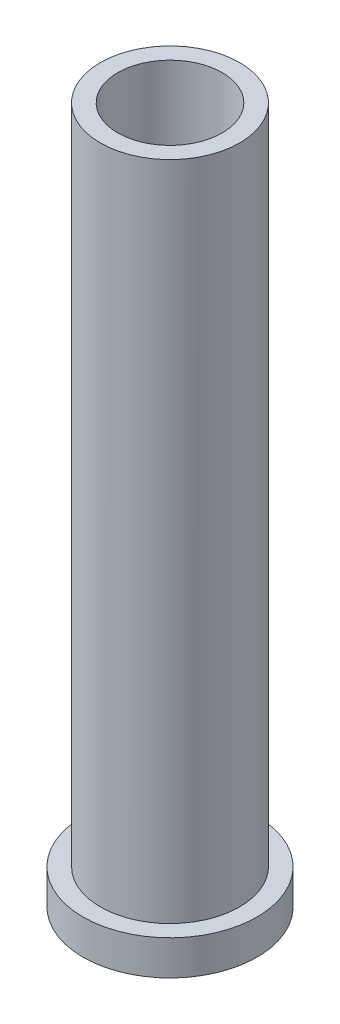
SolidWorks part; units mm, degrees
ref_plane "Front Plane" through (0, 0, 0) normal (0, 0, 1) x (1, 0, 0)
ref_plane "Top Plane" through (0, 0, 0) normal (0, 1, 0) x (1, 0, 0)
ref_plane "Right Plane" through (0, 0, 0) normal (1, 0, 0) x (0, 0, -1)
sketch "Sketch1" plane through (0, 0, 0) normal (0, 1, 0) x (1, 0, 0)
  circle A0 centre (0, 0) radius 4
  dimension "D1" = 8
extrude "Boss-Extrude1" add sketch "Sketch1" along normal blind 38
sketch "Sketch2" plane through (0, 0, 0) normal (0, -1, 0) x (1, 0, 0)
  circle A0 centre (0, 0) radius 5
  dimension "D1" = 10
extrude "Boss-Extrude2" add sketch "Sketch2" along normal blind 2
sketch "Sketch3" plane through (0, 38, 0) normal (0, 1, 0) x (1, 0, 0)
  circle A0 centre (0, 0) radius 3
  dimension "D1" = 6
extrude "Cut-Extrude1" cut sketch "Sketch3" against normal blind 41
